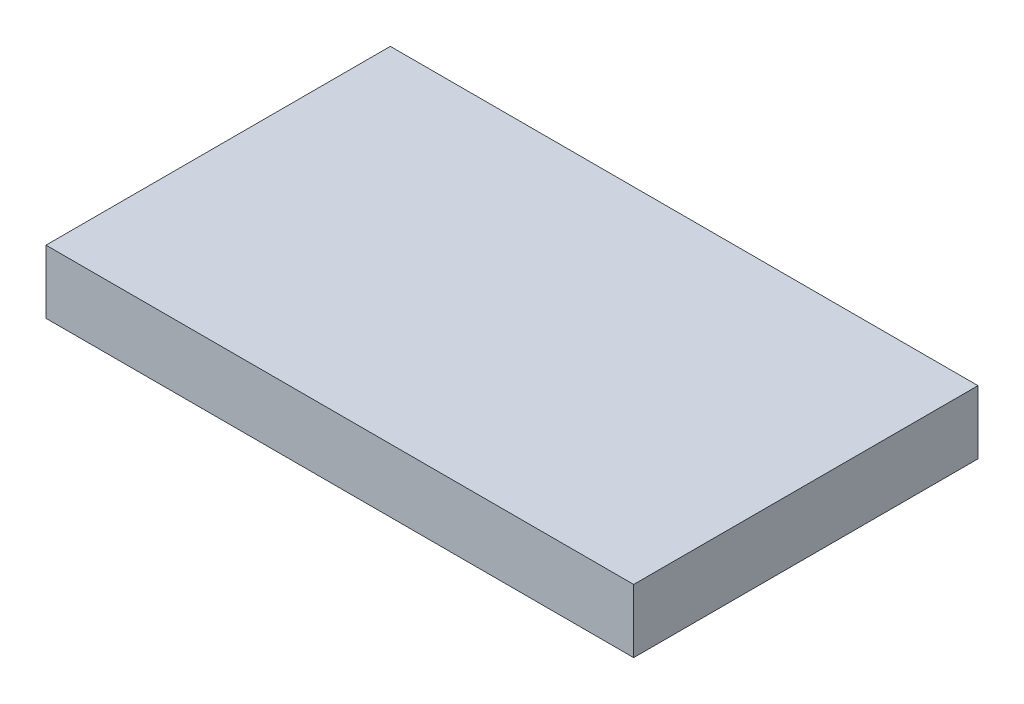
SolidWorks part; units mm, degrees
ref_plane "Front" through (0, 0, 0) normal (0, 0, 1) x (1, 0, 0)
ref_plane "Top" through (0, 0, 0) normal (0, 1, 0) x (1, 0, 0)
ref_plane "Right" through (0, 0, 0) normal (1, 0, 0) x (0, 0, -1)
sketch "Sketch1" plane through (0, 0, 0) normal (0, 1, 0) x (1, 0, 0)
  line L1 (-29.425, 17.24) -> (29.425, 17.24)
  line L2 (-29.425, 17.24) -> (-29.425, -17.24)
  line L3 (-29.425, -17.24) -> (29.425, -17.24)
  line L4 (29.425, 17.24) -> (29.425, -17.24)
  line L5 (-29.425, 17.24) -> (29.425, -17.24) construction
  line L6 (-29.425, -17.24) -> (29.425, 17.24) construction
  point P0 (0, 0)
  dimension "D1" = 58.85
  dimension "D2" = 34.48
extrude "Boss-Extrude1" add sketch "Sketch1" along normal blind 6.35
